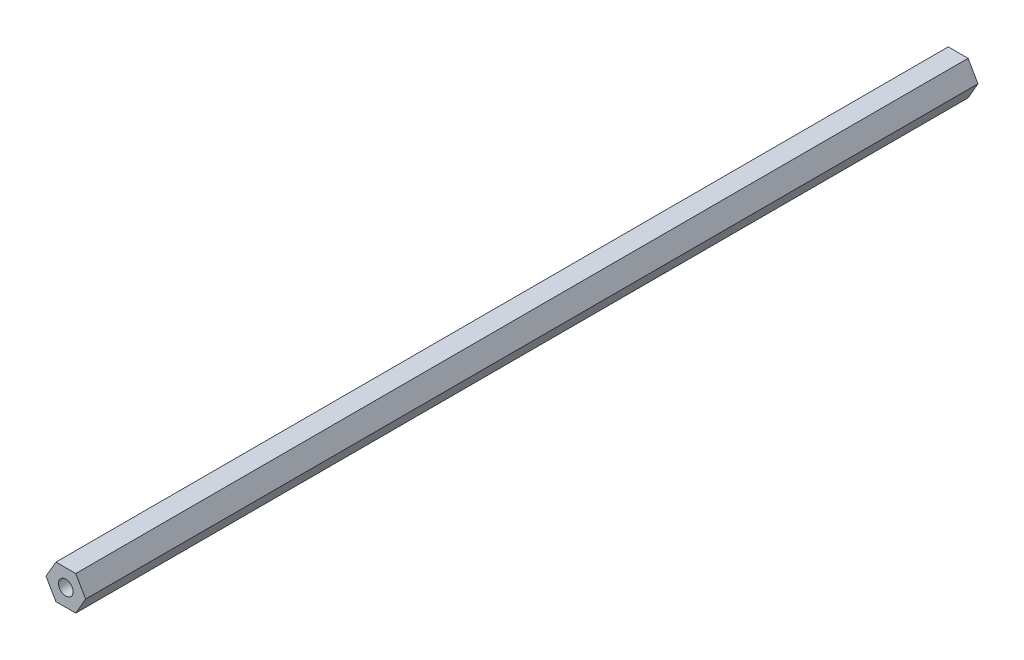
SolidWorks part; units mm, degrees
material "6061 Alloy"
ref_plane "Front Plane" through (0, 0, 0) normal (0, 0, 1) x (1, 0, 0)
ref_plane "Top Plane" through (0, 0, 0) normal (0, 1, 0) x (1, 0, 0)
ref_plane "Right Plane" through (0, 0, 0) normal (1, 0, 0) x (0, 0, -1)
sketch "Sketch1" plane through (0, 0, 0) normal (0, 0, 1) x (1, 0, 0)
  line L1 (7.3323, 0) -> (3.6662, 6.35)
  line L2 (3.6662, 6.35) -> (-3.6662, 6.35)
  line L3 (-3.6662, 6.35) -> (-7.3323, 0)
  line L4 (-7.3323, 0) -> (-3.6662, -6.35)
  line L5 (-3.6662, -6.35) -> (3.6662, -6.35)
  line L6 (3.6662, -6.35) -> (7.3323, 0)
  circle A0 centre (0, 0) radius 6.35 construction
  dimension "D1" = 12.7
extrude "Boss-Extrude1" add sketch "Sketch1" along normal mid plane 330.2
hole_wizard "1/4-28 Tapped Hole1" positions "3DSketch1" profile "Sketch2" tap size "1/4-28" standard "ANSI Inch"
sketch3d "3DSketch1"
  point P0 (0, 0, 165.1)
  point P2 (0, 0, -165.1)
sketch "Sketch2" plane through (0, 0, 165.1) normal (1, 0, 0) x (0, -1, 0)
  line L0 (0, 0) -> (0, 29.8194)
  line L1 (0, 29.8194) -> (2.7051, 28.194)
  line L2 (2.7051, 28.194) -> (2.7051, 0)
  line L5 (2.7051, 0) -> (0, 0)
  line L10 (0, 29.8194) -> (-2.7051, 28.194) construction
  line L11 (0, -6.35) -> (0, 107.95) construction
  dimension "Tap Drill Dia." = 5.4102
  dimension "Tap Drill Depth" = 28.194
  dimension "Drill Angle" = 118
